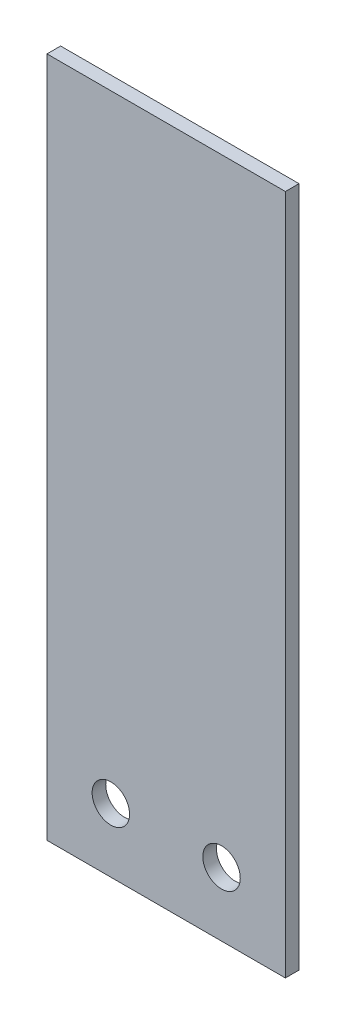
SolidWorks part; units mm, degrees
ref_plane "Front Plane" through (0, 0, 0) normal (0, 0, 1) x (1, 0, 0)
ref_plane "Top Plane" through (0, 0, 0) normal (0, 1, 0) x (1, 0, 0)
ref_plane "Right Plane" through (0, 0, 0) normal (1, 0, 0) x (0, 0, -1)
sketch "Sketch1" plane through (0, 0, 0) normal (0, 0, 1) x (1, 0, 0)
  line L1 (-14, -40) -> (14, -40)
  line L2 (-14, -40) -> (-14, 40)
  line L3 (-14, 40) -> (14, 40)
  line L4 (14, -40) -> (14, 40)
  line L5 (-14, -40) -> (14, 40) construction
  line L6 (-14, 40) -> (14, -40) construction
  point P0 (0, 0)
  dimension "D1" = 28
  dimension "D2" = 80
extrude "Boss-Extrude1" add sketch "Sketch1" along normal blind 1.6
sketch "Sketch2" plane through (0, 0, 1.6) normal (0, 0, 1) x (1, 0, 0)
  line L0 (-14, 40) -> (-14, -40) construction
  line L1 (14, -40) -> (14, 40) construction
  line L2 (-14, -40) -> (14, -40) construction
  circle A0 centre (6.5, -32.5) radius 2.2
  circle A1 centre (-6.5, -32.5) radius 2.2
  point P10 (0, 0)
  dimension "D1" = 4.4
  dimension "D2" = 7.5
  dimension "D3" = 7.5
  dimension "D4" = 7.5
extrude "Cut-Extrude1" cut sketch "Sketch2" against normal blind 10
